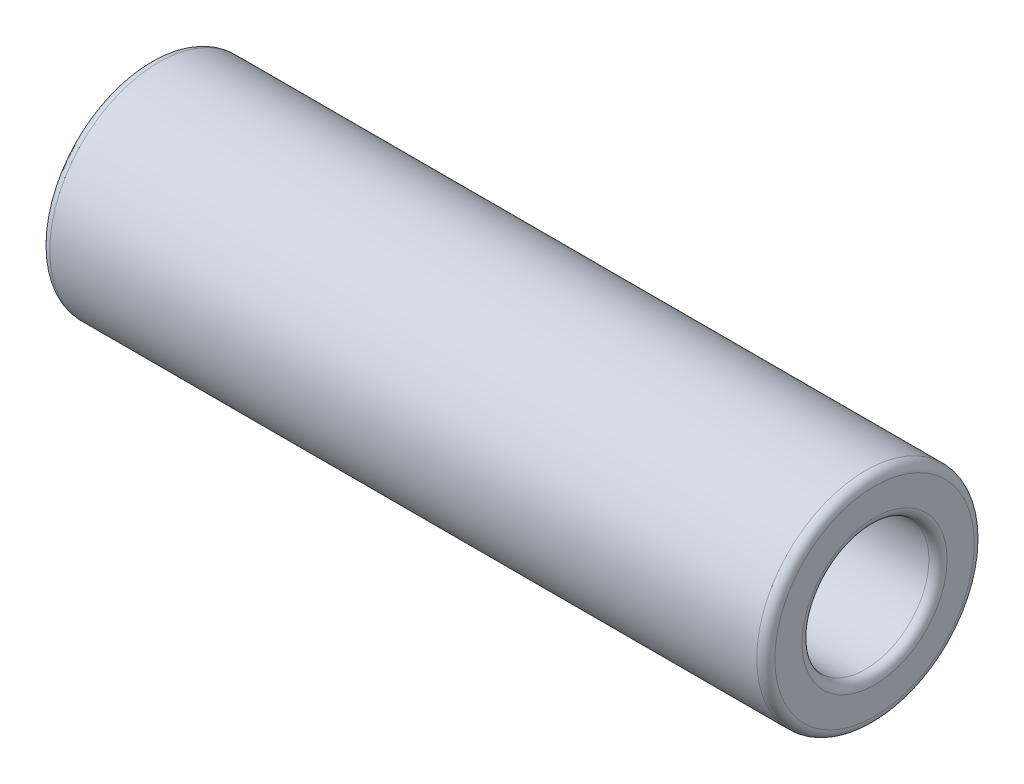
SolidWorks part; units mm, degrees
ref_plane "Płaszczyzna przednia" through (0, 0, 0) normal (0, 0, 1) x (1, 0, 0)
ref_plane "Płaszczyzna górna" through (0, 0, 0) normal (0, 1, 0) x (1, 0, 0)
ref_plane "Płaszczyzna prawa" through (0, 0, 0) normal (1, 0, 0) x (0, 0, -1)
sketch "Szkic1" plane through (0, 0, 0) normal (1, 0, 0) x (0, 0, -1)
  circle A0 centre (0, 0) radius 3.5
  circle A1 centre (0, 0) radius 6
  dimension "D1" = 7
  dimension "D2" = 12
extrude "Dodanie-wyciągnięcie1" add sketch "Szkic1" along normal blind 40
fillet "Zaokrąglenie1" radius 0.5 4 edges at (40, 0, -3.5) (40, 0, -6) (0, 0, -3.5) (0, 0, -6)
